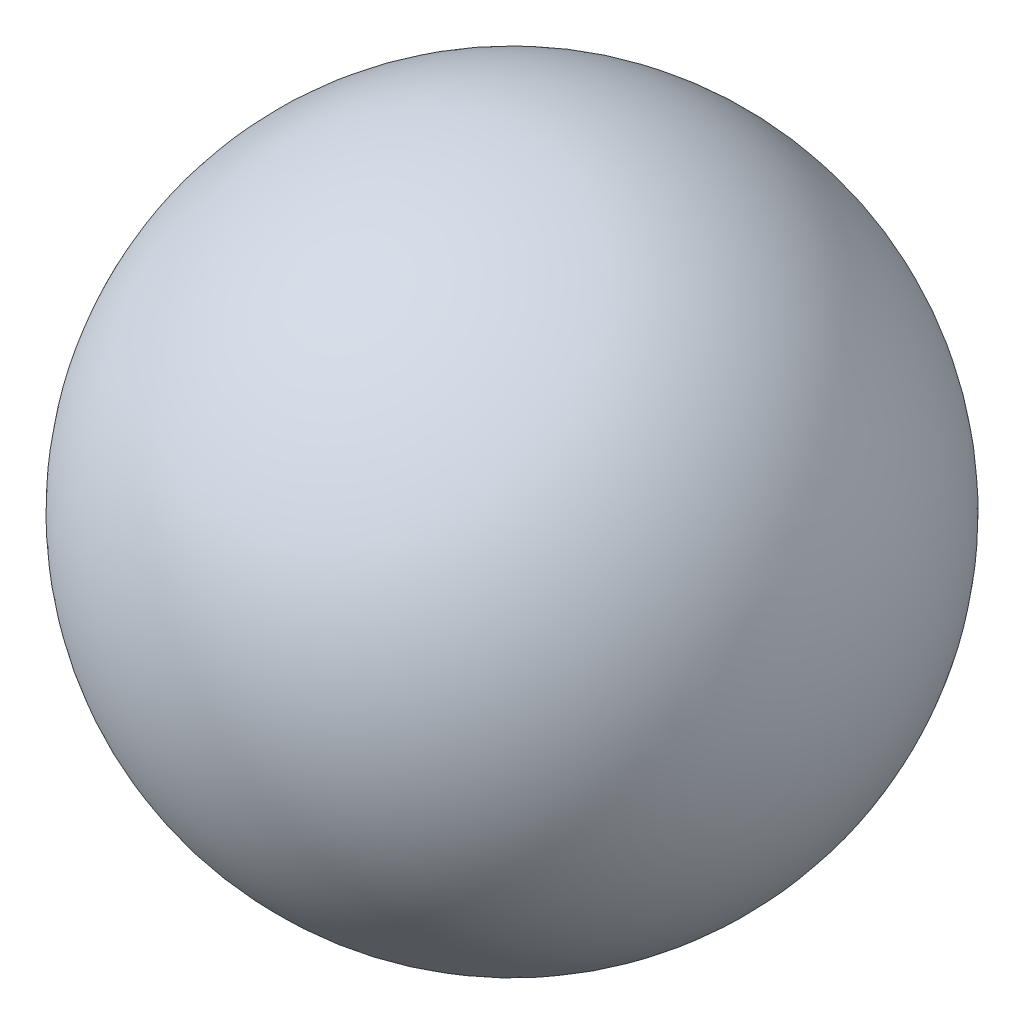
SolidWorks part; units mm, degrees
ref_plane "Front Plane" through (0, 0, 0) normal (0, 0, 1) x (1, 0, 0)
ref_plane "Top Plane" through (0, 0, 0) normal (0, 1, 0) x (1, 0, 0)
ref_plane "Right Plane" through (0, 0, 0) normal (1, 0, 0) x (0, 0, -1)
sketch "Sketch1" plane through (0, 0, 0) normal (0, 1, 0) x (1, 0, 0)
  line L0 (-43.775, 0) -> (43.775, 0) construction
  line L1 (43.775, 0) -> (-43.775, 0)
  arc A0 (43.775, 0) -> (-43.775, 0) centre (0, 0) ccw
  dimension "D1" = 87.55
revolve "Revolve1" add sketch "Sketch1" angle 360 about L0
